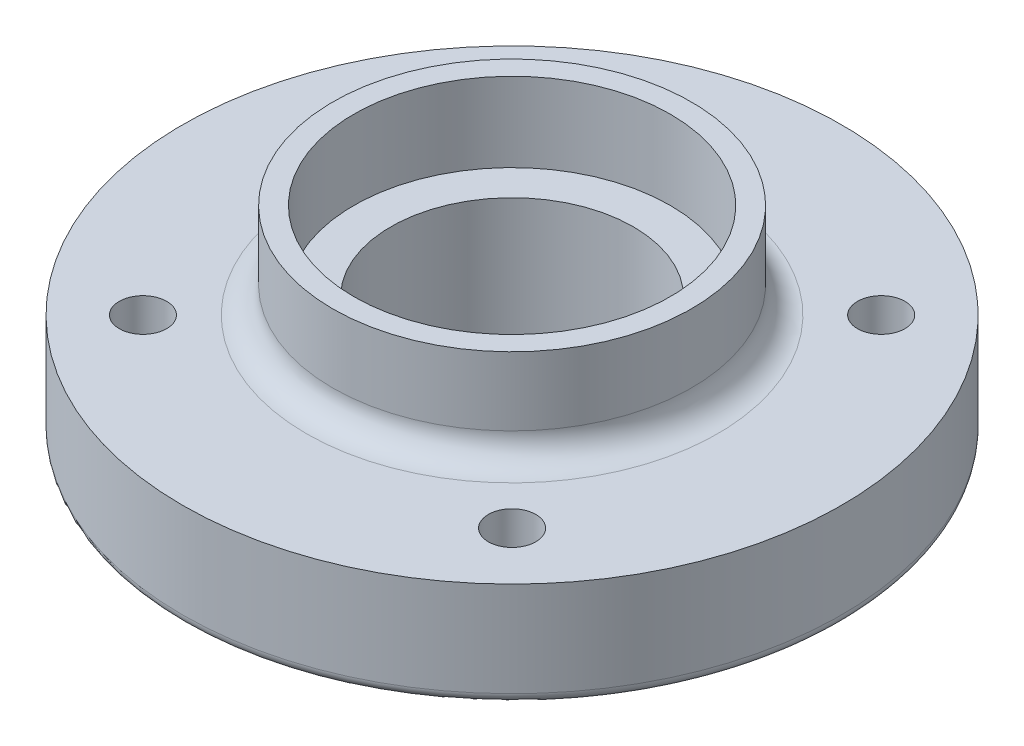
SolidWorks part; units mm, degrees
ref_plane "Front Plane" through (0, 0, 0) normal (0, 0, 1) x (1, 0, 0)
ref_plane "Top Plane" through (0, 0, 0) normal (0, 1, 0) x (1, 0, 0)
ref_plane "Right Plane" through (0, 0, 0) normal (1, 0, 0) x (0, 0, -1)
sketch "Sketch1" plane through (0, 0, 0) normal (0, 1, 0) x (1, 0, 0)
  circle A0 centre (0, 0) radius 62.5
  dimension "D1" = 125
extrude "Boss-Extrude1" add sketch "Sketch1" along normal blind 20
sketch "Sketch2" plane through (0, 20, 0) normal (0, 1, 0) x (1, 0, 0)
  circle A0 centre (0, 0) radius 34
  dimension "D1" = 68
extrude "Boss-Extrude2" add sketch "Sketch2" along normal blind 18
sketch "Sketch6" plane through (0, 38, 0) normal (0, 1, 0) x (1, 0, 0)
  circle A2 centre (0, 0) radius 30
  circle A3 centre (0, 0) radius 30
  dimension "D1" = 4
extrude "Cut-Extrude1" cut sketch "Sketch6" against normal blind 15
fillet "Fillet1" radius 5 1 edges at (0, 20, 34)
sketch "Sketch7" plane through (0, 0, 0) normal (0, -1, 0) x (1, 0, 0)
  line L1 (-35, 35) -> (35, 35) construction
  line L2 (-35, 35) -> (-35, -35) construction
  line L3 (-35, -35) -> (35, -35) construction
  line L4 (35, 35) -> (35, -35) construction
  line L5 (-35, 35) -> (35, -35) construction
  line L6 (-35, -35) -> (35, 35) construction
  point P0 (0, 0)
  dimension "D1" = 70
  dimension "D2" = 70
hole_wizard "CBORE for M8 Hex Head Bolt1" positions "3DSketch1" profile "Sketch12" counterbore size "M8" standard "ISO" end condition through all
sketch3d "3DSketch1"
  point P0 (-35, 0, 35)
  point P3 (35, 0, 35)
  point P6 (35, 0, -35)
  point P9 (-35, 0, -35)
sketch "Sketch12" plane through (-35, 0, 35) normal (1, 0, 0) x (0, 0, -1)
  line L0 (0, 0) -> (0, 38)
  line L1 (0, 38) -> (4.5, 38)
  line L3 (4.5, 38) -> (4.5, 5.3)
  line L4 (4.5, 5.3) -> (9.0055, 5.3)
  line L5 (9.0055, 5.3) -> (9.0055, 0)
  line L7 (9.0055, 0) -> (0, 0)
  line L11 (0, -6.35) -> (0, 107.95) construction
  dimension "Thru Hole Dia." = 9
  dimension "Thru Hole Depth" = 38
  dimension "C'Bore Dia." = 18.011
  dimension "C'Bore Depth" = 5.3
fillet "Fillet2" radius 2 1 edges at (0, 0, 62.5)
sketch "Sketch10" plane through (0, 23, 0) normal (0, 1, 0) x (1, 0, 0)
  circle A1 centre (0, 0) radius 23
  dimension "D1" = 46
extrude "Cut-Extrude2" cut sketch "Sketch10" against normal blind 53
sketch "Sketch11" plane through (0, 0, 0) normal (0, -1, 0) x (1, 0, 0)
  circle A0 centre (0, 0) radius 35
  circle A1 centre (0, 0) radius 23 construction
  circle A2 centre (0, 0) radius 23
  dimension "D1" = 70
extrude "Boss-Extrude3" add sketch "Sketch11" along normal blind 15 contours A0 | A2
fillet "Fillet3" radius 1 2 edges at (0, 0, 35) (0, -15, -35)
